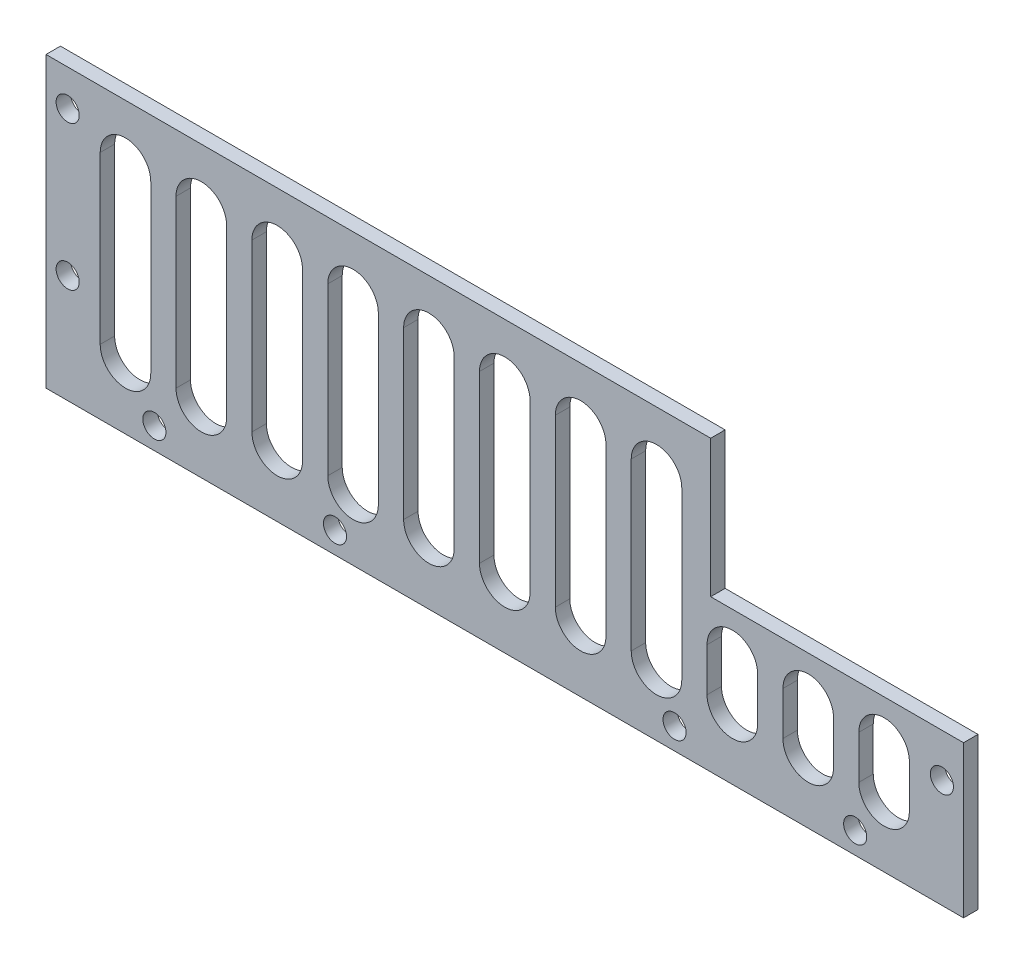
SolidWorks part; units mm, degrees
material "玻纤"
ref_plane "前视基准面" through (0, 0, 0) normal (0, 0, 1) x (1, 0, 0)
ref_plane "上视基准面" through (0, 0, 0) normal (0, 1, 0) x (1, 0, 0)
ref_plane "右视基准面" through (0, 0, 0) normal (1, 0, 0) x (0, 0, -1)
sketch "草图1" plane through (0, 0, 0) normal (0, 0, 1) x (1, 0, 0)
  line L0 (-60.5, 20) -> (-60.5, -20) construction
  line L1 (-63.5, -20) -> (63.5, -20)
  line L2 (-63.5, -20) -> (-63.5, 20)
  line L3 (-63.5, 20) -> (63.5, 20)
  line L4 (63.5, -20) -> (63.5, 20)
  line L5 (-63.5, -20) -> (63.5, 20) construction
  line L6 (-63.5, 20) -> (63.5, -20) construction
  line L7 (-57.5, 20) -> (-63.5, 20)
  line L8 (-57.5, 20) -> (-57.5, -20)
  line L9 (-57.5, -20) -> (-63.5, -20)
  line L10 (-63.5, 20) -> (-63.5, -20)
  line L11 (-57.5, 20) -> (-63.5, -20) construction
  line L12 (-57.5, -20) -> (-63.5, 20) construction
  line L13 (0, 0) -> (0, -20) construction
  line L14 (57.5, -20) -> (63.5, 20) construction
  line L15 (57.5, 20) -> (63.5, -20) construction
  line L16 (60.5, 20) -> (60.5, -20) construction
  line L17 (63.5, 20) -> (63.5, -20)
  line L18 (57.5, -20) -> (63.5, -20)
  line L19 (57.5, 20) -> (57.5, -20)
  line L20 (57.5, 20) -> (63.5, 20)
  circle A0 centre (-60.5, 15) radius 1.6
  circle A1 centre (-60.5, -5) radius 1.6
  circle A2 centre (60.5, -5) radius 1.6
  circle A3 centre (60.5, 15) radius 1.6
  point P0 (0, 0)
  point P5 (-60.5, 0)
  point P27 (60.5, 0)
  dimension "D3" = 15
  dimension "D4" = 20
  dimension "D5" = 5
  dimension "D7" = 3.2
  dimension "D8" = 3.2
  dimension "D1" = 6
  dimension "D2" = 127
  dimension "D6" = 40
extrude "凸台-拉伸1" add sketch "草图1" along normal blind 2 contours L19 L20 L4 L3 L2 L7 L8 L1 | L20 L19 L1 L4 A2 A3 | L8 L7 L2 L1 A1 A0
sketch "草图2" plane through (0, 0, 2) normal (0, 0, 1) x (1, 0, 0)
  line L0 (0, 12) -> (0, -11) construction
  line L1 (3.5, 12) -> (3.5, -11)
  line L2 (-3.5, 12) -> (-3.5, -11)
  line L3 (-63.5, -20) -> (63.5, -20) construction
  line L4 (-63.5, 20) -> (63.5, 20) construction
  line L5 (0, 0.5) -> (-25.8037, 0.5) construction
  line L6 (10.5, 12) -> (10.5, -11) construction
  line L7 (14, 12) -> (14, -11)
  line L8 (7, 12) -> (7, -11)
  line L9 (21, 12) -> (21, -11) construction
  line L10 (24.5, 12) -> (24.5, -11)
  line L11 (17.5, 12) -> (17.5, -11)
  line L18 (-10.5, 12) -> (-10.5, -11) construction
  line L19 (-7, 12) -> (-7, -11)
  line L20 (-14, 12) -> (-14, -11)
  line L21 (-21, 12) -> (-21, -11) construction
  line L22 (-17.5, 12) -> (-17.5, -11)
  line L23 (-24.5, 12) -> (-24.5, -11)
  line L24 (-31.5, 12) -> (-31.5, -11) construction
  line L25 (-28, 12) -> (-28, -11)
  line L26 (-35, 12) -> (-35, -11)
  line L27 (-42, 12) -> (-42, -11) construction
  line L28 (-38.5, 12) -> (-38.5, -11)
  line L29 (-45.5, 12) -> (-45.5, -11)
  line L30 (-52.5, 12) -> (-52.5, -11) construction
  line L31 (-49, 12) -> (-49, -11)
  line L32 (-56, 12) -> (-56, -11)
  arc A0 (3.5, 12) -> (-3.5, 12) centre (0, 12) ccw
  arc A1 (-3.5, -11) -> (3.5, -11) centre (0, -11) ccw
  arc A2 (14, 12) -> (7, 12) centre (10.5, 12) ccw
  arc A3 (7, -11) -> (14, -11) centre (10.5, -11) ccw
  arc A4 (24.5, 12) -> (17.5, 12) centre (21, 12) ccw
  arc A5 (17.5, -11) -> (24.5, -11) centre (21, -11) ccw
  arc A10 (-7, 12) -> (-14, 12) centre (-10.5, 12) ccw
  arc A11 (-14, -11) -> (-7, -11) centre (-10.5, -11) ccw
  arc A12 (-17.5, 12) -> (-24.5, 12) centre (-21, 12) ccw
  arc A13 (-24.5, -11) -> (-17.5, -11) centre (-21, -11) ccw
  arc A14 (-28, 12) -> (-35, 12) centre (-31.5, 12) ccw
  arc A15 (-35, -11) -> (-28, -11) centre (-31.5, -11) ccw
  arc A16 (-38.5, 12) -> (-45.5, 12) centre (-42, 12) ccw
  arc A17 (-45.5, -11) -> (-38.5, -11) centre (-42, -11) ccw
  arc A18 (-49, 12) -> (-56, 12) centre (-52.5, 12) ccw
  arc A19 (-56, -11) -> (-49, -11) centre (-52.5, -11) ccw
  point P3 (0, 0.5)
  point P17 (10.5, 0.5)
  point P24 (21, 0.5)
  point P45 (-10.5, 0.5)
  point P52 (-21, 0.5)
  point P59 (-31.5, 0.5)
  point P66 (-42, 0.5)
  point P72 (-52.5, 0.5)
  dimension "D1" = 3.5
  dimension "D2" = 9
  dimension "D3" = 8
  dimension "D4" = 3
  dimension "D6" = 10.5
  dimension "D7" = 10.5
  dimension "D5" = 6
extrude "切除-拉伸1" cut sketch "草图2" against normal blind 2
sketch "草图3" plane through (0, 0, 2) normal (0, 0, 1) x (1, 0, 0)
  line L0 (-63.5, -17) -> (63.5, -17) construction
  line L1 (-63.5, -20) -> (-63.5, 20) construction
  line L2 (63.5, -20) -> (63.5, 20) construction
  line L3 (0, -20) -> (0, 20) construction
  line L4 (-63.5, -20) -> (63.5, -20) construction
  line L5 (-63.5, 20) -> (63.5, 20) construction
  circle A0 centre (-48.5, -17) radius 1.6
  circle A1 centre (-23.5, -17) radius 1.6
  circle A2 centre (-60.5, -5) radius 1.6 construction
  circle A3 centre (23.5, -17) radius 1.6
  circle A4 centre (48.5, -17) radius 1.6
  dimension "D2" = 15
  dimension "D1" = 3
  dimension "D3" = 25
extrude "切除-拉伸2" cut sketch "草图3" against normal through all
sketch "草图4" plane through (0, 0, 2) normal (0, 0, 1) x (1, 0, 0)
  line L0 (63.5, -20) -> (63.5, 20) construction
  line L1 (63.5, 5.4) -> (33.5, 5.4)
  line L2 (63.5, 5.4) -> (63.5, 11.4)
  line L3 (63.5, 11.4) -> (33.5, 11.4)
  line L4 (31.5, 5.4) -> (31.5, 11.4)
  line L5 (-63.5, -20) -> (63.5, -20) construction
  arc A0 (31.5, 11.4) -> (33.5, 11.4) centre (32.5, 11.4) cw
  arc A1 (31.5, 5.4) -> (33.5, 5.4) centre (32.5, 5.4) ccw
  dimension "D4" = 1
  dimension "D1" = 32
  dimension "D2" = 31.4
  dimension "D3" = 6
extrude "切除-拉伸3" cut sketch "草图4" against normal through all
sketch "草图5" plane through (0, 0, 2) normal (0, 0, 1) x (1, 0, 0)
  line L0 (31.5, -5) -> (31.5, -11) construction
  line L1 (35, -5) -> (35, -11)
  line L2 (28, -5) -> (28, -11)
  line L3 (42, -5) -> (42, -11) construction
  line L4 (45.5, -5) -> (45.5, -11)
  line L5 (38.5, -5) -> (38.5, -11)
  line L6 (52.5, -5) -> (52.5, -11) construction
  line L7 (56, -5) -> (56, -11)
  line L8 (49, -5) -> (49, -11)
  arc A0 (35, -5) -> (28, -5) centre (31.5, -5) ccw
  arc A1 (28, -11) -> (35, -11) centre (31.5, -11) ccw
  arc A2 (17.5, -11) -> (24.5, -11) centre (21, -11) ccw construction
  arc A3 (45.5, -5) -> (38.5, -5) centre (42, -5) ccw
  arc A4 (38.5, -11) -> (45.5, -11) centre (42, -11) ccw
  arc A5 (56, -5) -> (49, -5) centre (52.5, -5) ccw
  arc A6 (49, -11) -> (56, -11) centre (52.5, -11) ccw
  point P2 (31.5, -8)
  point P14 (42, -8)
  point P21 (52.5, -8)
  dimension "D1" = 10.5
  dimension "D2" = 6
  dimension "D4" = 10.5
  dimension "D3" = 3
extrude "切除-拉伸4" cut sketch "草图5" against normal through all
sketch "草图6" plane through (0, 0, 2) normal (0, 0, 1) x (1, 0, 0)
  line L1 (28.5, 1) -> (63.5, 1)
  line L2 (28.5, 1) -> (28.5, 20)
  line L3 (28.5, 20) -> (63.5, 20)
  line L4 (63.5, 1) -> (63.5, 20)
  dimension "D1" = 19
  dimension "D2" = 35
extrude "切除-拉伸5" cut sketch "草图6" against normal through all
